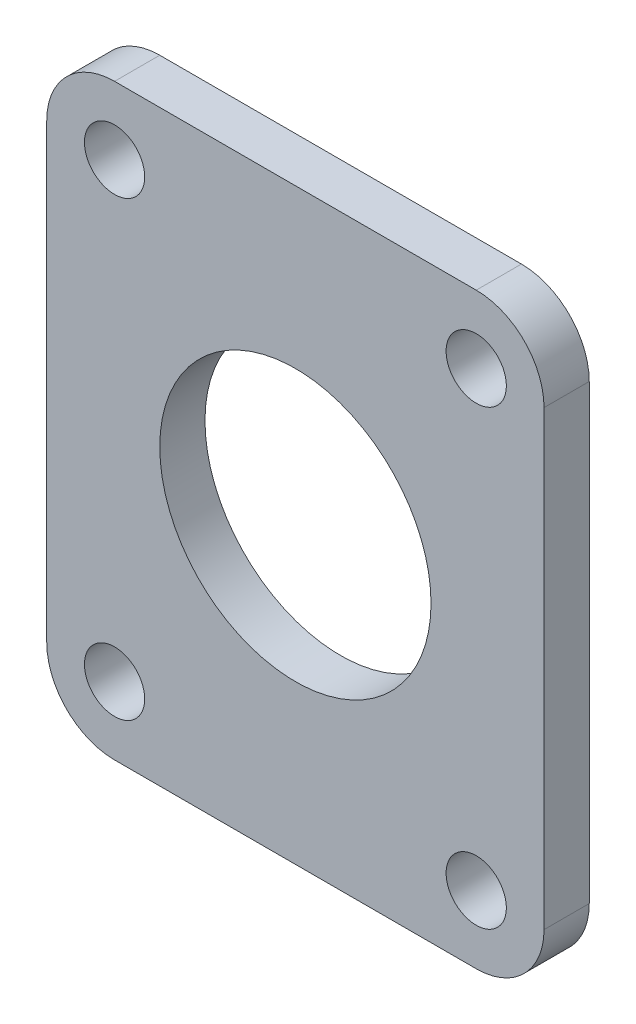
SolidWorks part; units mm, degrees
ref_plane "Alzado" through (0, 0, 0) normal (0, 0, 1) x (1, 0, 0)
ref_plane "Planta" through (0, 0, 0) normal (0, 1, 0) x (1, 0, 0)
ref_plane "Vista lateral" through (0, 0, 0) normal (1, 0, 0) x (0, 0, -1)
sketch "Model" plane through (0, 0, 0) normal (0, 0, 1) x (1, 0, 0)
  line L0 (648.871, 460.456) -> (648.871, 430.456)
  line L1 (653.371, 425.956) -> (677.371, 425.956)
  line L2 (681.871, 430.456) -> (681.871, 460.456)
  line L3 (677.371, 464.956) -> (653.371, 464.956)
  circle A0 centre (677.371, 430.456) radius 2
  circle A1 centre (677.371, 460.456) radius 2
  circle A2 centre (653.371, 460.456) radius 2
  circle A3 centre (653.371, 430.456) radius 2
  circle A4 centre (665.371, 445.456) radius 9
  arc A5 (653.371, 464.956) -> (648.871, 460.456) centre (653.371, 460.456) ccw
  arc A6 (681.871, 460.456) -> (677.371, 464.956) centre (677.371, 460.456) ccw
  arc A7 (677.371, 425.956) -> (681.871, 430.456) centre (677.371, 430.456) ccw
  arc A8 (648.871, 430.456) -> (653.371, 425.956) centre (653.371, 430.456) ccw
extrude "Saliente-Extruir1" add sketch "Model" along normal blind 3
